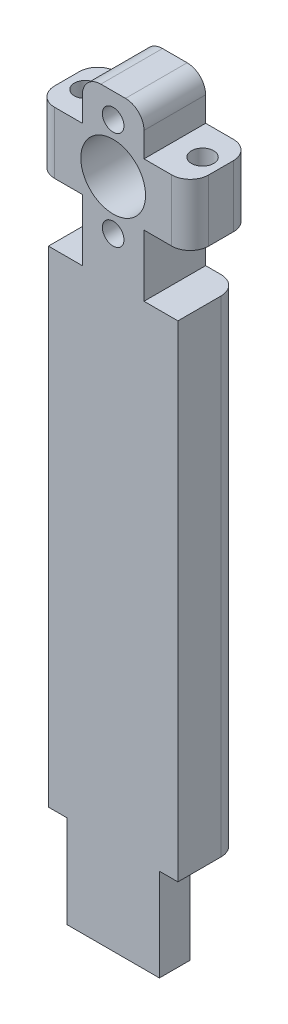
SolidWorks part; units mm, degrees
ref_plane "前视基准面" through (0, 0, 0) normal (0, 0, 1) x (1, 0, 0)
ref_plane "上视基准面" through (0, 0, 0) normal (0, 1, 0) x (1, 0, 0)
ref_plane "右视基准面" through (0, 0, 0) normal (1, 0, 0) x (0, 0, -1)
other "Configuration Table"
sketch "草图1" plane through (0, 0, 0) normal (0, 0, 1) x (1, 0, 0)
  line L1 (-5, -15) -> (5, -15)
  line L2 (-5, -15) -> (-5, 12)
  line L3 (-5, 12) -> (5, 12)
  line L4 (5, -15) -> (5, 12)
  line L7 (-12.5, 5) -> (12.5, 5)
  line L8 (-12.5, 5) -> (-12.5, -5)
  line L9 (-12.5, -5) -> (12.5, -5)
  line L10 (12.5, 5) -> (12.5, -5)
  line L11 (-12.5, 5) -> (12.5, -5) construction
  line L12 (-12.5, -5) -> (12.5, 5) construction
  point P0 (0, 0)
  point P6 (0, 0)
  dimension "D1" = 10
  dimension "D2" = 10
  dimension "D3" = 25
  dimension "D4" = 15
  dimension "D5" = 12
extrude "凸台-拉伸1" add sketch "草图1" along normal blind 10 contours L8 L9 L2 L7 | L2 L9 L4 L7 | L2 L7 L4 L3 | L10 L7 L4 L9 | L9 L2 L1 L4
sketch "草图2" plane through (0, -5, 0) normal (0, -1, 0) x (1, 0, 0)
  line L0 (-15, 5) -> (49985, 5) construction
  line L1 (-12.5, 10) -> (-12.5, 0) construction
  line L2 (0, 10) -> (0, -49990) construction
  line L3 (-5, 10) -> (5, 10) construction
  circle A0 centre (-9.5, 5) radius 1.8
  circle A1 centre (9.5, 5) radius 1.8
  point P4 (-12.5, 5)
  point P9 (0, 10)
  dimension "D1" = 3.6
  dimension "D2" = 3
extrude "切除-拉伸1" cut sketch "草图2" against normal up to next
sketch "草图3" plane through (0, 0, 0) normal (0, 0, -1) x (-1, 0, 0)
  circle A0 centre (0, 0) radius 5.25
  dimension "D1" = 10.5
extrude "切除-拉伸2" cut sketch "草图3" against normal up to next
sketch "草图4" plane through (0, 0, 0) normal (0, 0, -1) x (-1, 0, 0)
  circle A0 centre (0, 0) radius 8 construction
  circle A1 centre (-8, 0) radius 1.75
  circle A2 centre (8, 0) radius 1.75
  dimension "D1" = 16
  dimension "D2" = 3.5
  dimension "D3" = 3.5
extrude "切除-拉伸3" [suppressed] cut sketch "草图4" against normal up to next
fillet "圆角1" radius 3 4 edges at (12.5, 0, 0) (12.5, 0, 10) (-12.5, 0, 10) (-12.5, 0, 0)
sketch "草图5" plane through (0, 0, 10) normal (0, 0, 1) x (1, 0, 0)
  circle A0 centre (0, 0) radius 8 construction
  circle A1 centre (0, 8) radius 1.75
  circle A2 centre (0, -8) radius 1.75
  dimension "D1" = 16
  dimension "D2" = 3.5
  dimension "D3" = 3.5
extrude "切除-拉伸4" cut sketch "草图5" against normal up to next
sketch "草图6" plane through (0, -15, 0) normal (0, -1, 0) x (1, 0, 0)
  line L4 (0, 0) -> (0, -50000) construction
  line L6 (-5, 0) -> (5, 0) construction
  line L12 (-5, 10) -> (5, 10) construction
  line L13 (-7.5, 0) -> (7.5, 0)
  line L14 (-7.5, 0) -> (-7.5, 10)
  line L18 (-7.5, 10) -> (7.5, 10)
  line L19 (7.5, 0) -> (7.5, 10)
  point P4 (0, 0)
  point P9 (0, 0)
  dimension "D1" = 15
extrude "凸台-拉伸2" add sketch "草图6" along normal blind 93.8
sketch "草图7" plane through (0, 0, 0) normal (0, 0, -1) x (-1, 0, 0)
  line L0 (7.5, -108.8) -> (7.5, -15) construction
  line L1 (-7.5, -108.8) -> (7.5, -108.8) construction
  line L2 (-7.5, -108.8) -> (-7.5, -93.8) construction
  line L3 (-7.5, -93.8) -> (7.5, -93.8) construction
  line L4 (7.5, -108.8) -> (7.5, -93.8) construction
  line L5 (0, -65) -> (0, 49935) construction
  line L6 (-5, -15) -> (-7.5, -15) construction
  line L7 (-10.5, -93.8) -> (10.5, -93.8)
  line L8 (-10.5, -93.8) -> (-10.5, -15)
  line L9 (-10.5, -15) -> (10.5, -15)
  line L10 (10.5, -93.8) -> (10.5, -15)
  line L11 (-7.5, -108.8) -> (-7.5, -15) construction
  point P9 (0, -108.8)
  point P14 (0, -15)
  dimension "D1" = 15
  dimension "D2" = 3
extrude "凸台-拉伸3" add sketch "草图7" against normal up to surface (10 mm away) up to face at (1.75, 8, 10)
fillet "圆角2" radius 3 2 edges at (-10.5, -54.4, 0) (10.5, -54.4, 0)
sketch "草图8" plane through (0, 0, 0) normal (0, 0, -1) x (-1, 0, 0)
  line L0 (7.5, -93.8) -> (-7.5, -93.8)
  line L18 (7.5, -108.8) -> (7.5, -93.8)
  line L19 (7.5, -93.8) -> (7.5, -15)
  line L20 (7.5, -15) -> (5, -15)
  line L21 (5, -15) -> (5, -5)
  line L22 (5, -5) -> (9.5, -5)
  line L23 (9.5, -5) -> (9.5, 5)
  line L24 (9.5, 5) -> (5, 5)
  line L25 (5, 5) -> (5, 12)
  line L26 (5, 12) -> (-5, 12)
  line L27 (-5, 12) -> (-5, 5)
  line L28 (-5, 5) -> (-9.5, 5)
  line L29 (-9.5, 5) -> (-9.5, -5)
  line L30 (-9.5, -5) -> (-5, -5)
  line L31 (-5, -5) -> (-5, -15)
  line L32 (-5, -15) -> (-7.5, -15)
  line L33 (-7.5, -15) -> (-7.5, -93.8)
  line L34 (-7.5, -93.8) -> (-7.5, -108.8)
  line L35 (-7.5, -108.8) -> (7.5, -108.8)
  line L36 (7.5, -108.8) -> (7.5, -93.8)
  line L52 (-7.5, -93.8) -> (-7.5, -108.8)
  line L53 (-7.5, -108.8) -> (7.5, -108.8)
  dimension "D1" = 0
extrude "切除-拉伸5" cut sketch "草图8" against normal blind 5
fillet "圆角3" radius 3 2 edges at (-5, 12, 5) (5, 12, 5)
